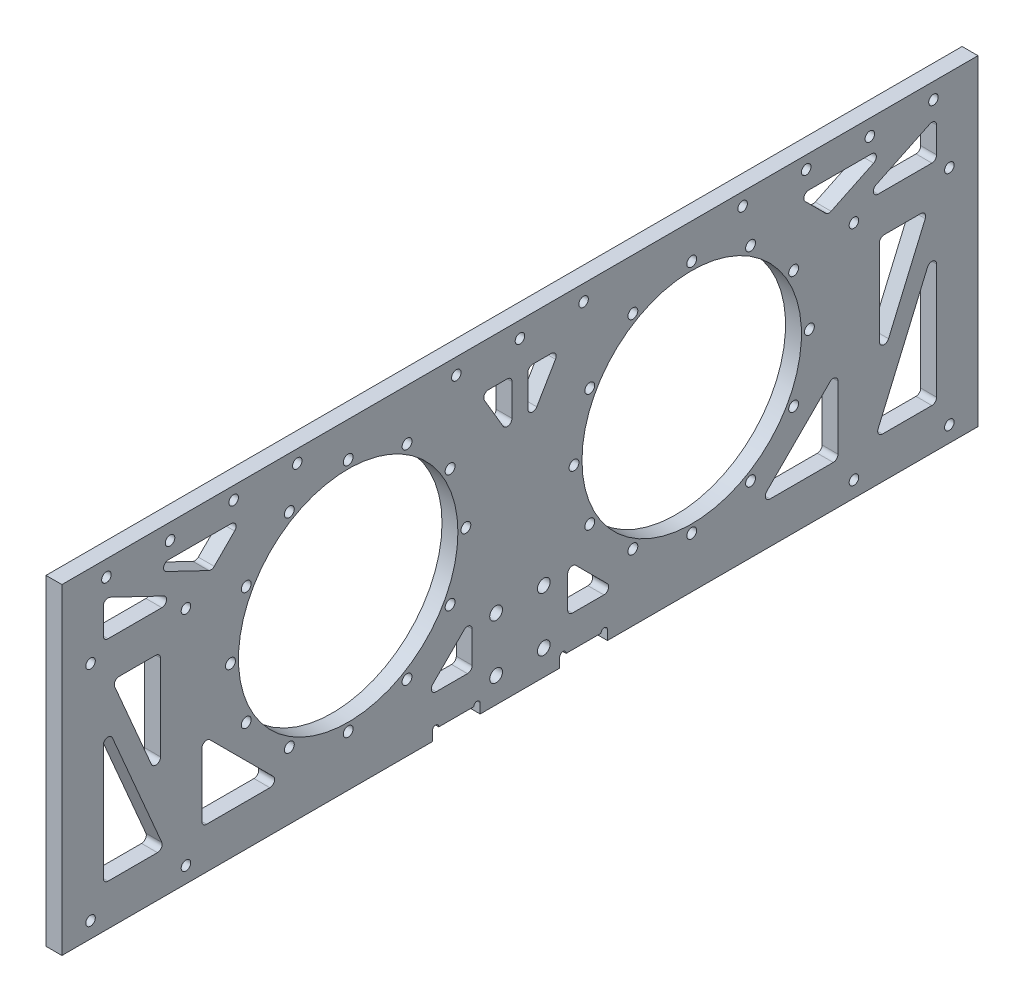
SolidWorks part; units mm, degrees
material "Thornel Mat VMA"
ref_plane "前视基准面" through (0, 0, 0) normal (0, 0, 1) x (1, 0, 0)
ref_plane "上视基准面" through (0, 0, 0) normal (0, 1, 0) x (1, 0, 0)
ref_plane "右视基准面" through (0, 0, 0) normal (1, 0, 0) x (0, 0, -1)
sketch "草图1" plane through (0, 0, 0) normal (1, 0, 0) x (0, 0, -1)
  line L0 (54, 48) -> (54, -53) construction
  line L1 (-90, -53) -> (198, -53)
  line L2 (-90, -53) -> (-90, 48)
  line L3 (-90, 48) -> (198, 48)
  line L4 (198, -53) -> (198, 48)
  line L5 (-36, 44) -> (-16, 44) construction
  line L6 (46.5, -45) -> (61.5, -45) construction
  line L7 (46.5, -45) -> (46.5, -28) construction
  line L8 (46.5, -28) -> (61.5, -28) construction
  line L9 (61.5, -45) -> (61.5, -28) construction
  line L10 (46.5, -45) -> (61.5, -28) construction
  line L11 (46.5, -28) -> (61.5, -45) construction
  line L12 (144, 44) -> (124, 44) construction
  circle A0 centre (0, 0) radius 34.5
  circle A1 centre (0, 0) radius 37 construction
  circle A2 centre (0, 37) radius 1.55
  circle A3 centre (18.5, 32.0429) radius 1.55
  circle A4 centre (32.0429, 18.5) radius 1.55
  circle A5 centre (37, 0) radius 1.55
  circle A6 centre (32.0429, -18.5) radius 1.55
  circle A7 centre (18.5, -32.0429) radius 1.55
  circle A8 centre (0, -37) radius 1.55
  circle A9 centre (-18.5, -32.0429) radius 1.55
  circle A10 centre (-32.0429, -18.5) radius 1.55
  circle A11 centre (-37, 0) radius 1.55
  circle A12 centre (-32.0429, 18.5) radius 1.55
  circle A13 centre (-18.5, 32.0429) radius 1.55
  circle A14 centre (126.5, 32.0429) radius 1.55
  circle A15 centre (140.0429, 18.5) radius 1.55
  circle A16 centre (145, 0) radius 1.55
  circle A17 centre (140.0429, -18.5) radius 1.55
  circle A18 centre (126.5, -32.0429) radius 1.55
  circle A19 centre (108, -37) radius 1.55
  circle A20 centre (89.5, -32.0429) radius 1.55
  circle A21 centre (75.9571, -18.5) radius 1.55
  circle A22 centre (71, 0) radius 1.55
  circle A23 centre (75.9571, 18.5) radius 1.55
  circle A24 centre (89.5, 32.0429) radius 1.55
  circle A25 centre (108, 37) radius 1.55
  circle A26 centre (108, 0) radius 37 construction
  circle A27 centre (108, 0) radius 34.5
  circle A28 centre (0, 0) radius 46 construction
  circle A29 centre (108, 0) radius 46 construction
  circle A30 centre (61.5, -28) radius 2
  circle A31 centre (46.5, -28) radius 2
  circle A32 centre (46.5, -45) radius 2
  circle A33 centre (61.5, -45) radius 2
  circle A34 centre (-16, 44) radius 1.5
  circle A35 centre (-36, 44) radius 1.5
  circle A36 centre (124, 44) radius 1.5
  circle A37 centre (144, 44) radius 1.5
  point P63 (54, -36.5)
  dimension "D1" = 69
  dimension "D2" = 74
  dimension "D4" = 3.1
  dimension "D9" = 92
  dimension "D13" = 4
  dimension "D17" = 3
  dimension "D5" = 53
  dimension "D6" = 48
  dimension "D7" = 90
  dimension "D8" = 108
  dimension "D10" = 25
  dimension "D11" = 17
  dimension "D12" = 15
  dimension "D14" = 70
  dimension "D15" = 20
  dimension "D16" = 4
  dimension "D3" = 12
extrude "凸台-拉伸1" add sketch "草图1" along normal blind 5
sketch "草图2" plane through (5, 0, 0) normal (1, 0, 0) x (0, 0, -1)
  line L0 (-76, 43) -> (-56, 43) construction
  line L1 (54, 48) -> (54, -53) construction
  line L2 (198, 48) -> (-90, 48) construction
  line L3 (-90, -53) -> (198, -53) construction
  line L4 (184, 43) -> (164, 43) construction
  line L5 (-90, 48) -> (-90, -53) construction
  line L6 (34, 43) -> (54, 43) construction
  circle A0 centre (-76, 43) radius 1.5
  circle A1 centre (-56, 43) radius 1.5
  circle A2 centre (164, 43) radius 1.5
  circle A3 centre (184, 43) radius 1.5
  circle A4 centre (34, 43) radius 1.5
  circle A5 centre (54, 43) radius 1.5
  circle A6 centre (74, 43) radius 1.5
  dimension "D1" = 14
  dimension "D4" = 3
  dimension "D6" = 3
  dimension "D2" = 20
  dimension "D3" = 5
  dimension "D5" = 20
extrude "切除-拉伸1" cut sketch "草图2" against normal through all
sketch "草图3" plane through (5, 0, 0) normal (1, 0, 0) x (0, 0, -1)
  line L0 (-81, -48) -> (-51, -48) construction
  line L1 (-90, 48) -> (-90, -53) construction
  line L2 (-90, -53) -> (198, -53) construction
  line L3 (54, 48) -> (54, -53) construction
  line L4 (198, 48) -> (-90, 48) construction
  line L5 (-81, -48) -> (-81, 22) construction
  line L6 (-81, 22) -> (-51, 22) construction
  line L7 (-51, 22) -> (-51, -48) construction
  line L8 (159, 22) -> (159, -48) construction
  line L9 (189, 22) -> (159, 22) construction
  line L10 (189, -48) -> (189, 22) construction
  line L11 (189, -48) -> (159, -48) construction
  circle A0 centre (-81, -48) radius 1.5
  circle A1 centre (-51, -48) radius 1.5
  circle A2 centre (-81, 22) radius 1.5
  circle A3 centre (-51, 22) radius 1.5
  circle A4 centre (159, 22) radius 1.5
  circle A5 centre (189, 22) radius 1.5
  circle A6 centre (159, -48) radius 1.5
  circle A7 centre (189, -48) radius 1.5
  dimension "D3" = 3
  dimension "D1" = 9
  dimension "D2" = 5
  dimension "D4" = 30
  dimension "D5" = 70
extrude "切除-拉伸2" cut sketch "草图3" against normal blind 10
sketch "草图4" plane through (5, 0, 0) normal (1, 0, 0) x (0, 0, -1)
  line L0 (44.1226, 34) -> (50, 34)
  line L1 (51.5, 32.5) -> (51.5, 22.5085)
  line L2 (48.7071, 21.7479) -> (42.8297, 31.7395)
  line L3 (54, 48) -> (54, -53) construction
  line L4 (198, 48) -> (-90, 48) construction
  line L5 (-90, -53) -> (198, -53) construction
  line L6 (56.5, 32.5) -> (56.5, 22.5085)
  line L7 (63.8774, 34) -> (58, 34)
  line L8 (59.2929, 21.7479) -> (65.1703, 31.7395)
  line L9 (-77, -2.257) -> (-77, -38.5)
  line L10 (-81, 22) -> (-51, 22) construction
  line L11 (-81, 22) -> (-81, -48) construction
  line L12 (-81, -48) -> (-51, -48) construction
  line L13 (-51, 22) -> (-51, -48) construction
  line L14 (-75.5, -40) -> (-59.9673, -40)
  line L15 (-58.5886, -37.9091) -> (-74.1213, -1.6661)
  line L16 (-72.0327, 14) -> (-60.5, 14)
  line L17 (-59, 12.5) -> (-59, -14.4097)
  line L18 (-61.8787, -15.0006) -> (-73.4114, 11.9091)
  line L19 (-46, -18.6213) -> (-46, -38.5)
  line L20 (-44.5, -40) -> (-24.6213, -40)
  line L21 (-23.5607, -37.4393) -> (-43.4393, -17.5607)
  line L22 (-77, 35.6161) -> (-77, 27.5)
  line L23 (-75.5, 26) -> (-58.5914, 26)
  line L24 (-57.9423, 28.8523) -> (-74.8509, 36.9684)
  line L25 (-56.5432, 38) -> (-36.7559, 38)
  line L26 (-35.6952, 35.4393) -> (-42.1127, 29.0218)
  line L27 (-43.8225, 28.7302) -> (-57.1923, 35.1477)
  line L34 (27.6213, -40) -> (37.5, -40)
  line L35 (39, -38.5) -> (39, -28.6213)
  line L36 (36.4393, -27.5607) -> (26.5607, -37.4393)
  line L37 (71.5607, -27.5607) -> (81.4393, -37.4393)
  line L38 (69, -38.5) -> (69, -28.6213)
  line L39 (80.3787, -40) -> (70.5, -40)
  line L40 (159, 22) -> (159, -48) construction
  line L41 (189, -48) -> (159, -48) construction
  line L42 (189, 22) -> (189, -48) construction
  line L43 (189, 22) -> (159, 22) construction
  line L50 (151.8225, 28.7302) -> (165.1923, 35.1477)
  line L51 (143.6952, 35.4393) -> (150.1127, 29.0218)
  line L52 (164.5432, 38) -> (144.7559, 38)
  line L53 (165.9423, 28.8523) -> (182.8509, 36.9684)
  line L54 (183.5, 26) -> (166.5914, 26)
  line L55 (185, 35.6161) -> (185, 27.5)
  line L56 (131.5607, -37.4393) -> (151.4393, -17.5607)
  line L57 (152.5, -40) -> (132.6213, -40)
  line L58 (154, -18.6213) -> (154, -38.5)
  line L59 (169.8787, -15.0006) -> (181.4114, 11.9091)
  line L60 (167, 12.5) -> (167, -14.4097)
  line L61 (180.0327, 14) -> (168.5, 14)
  line L62 (166.5886, -37.9091) -> (182.1213, -1.6661)
  line L63 (183.5, -40) -> (167.9673, -40)
  line L64 (185, -2.257) -> (185, -38.5)
  arc A0 (51.5, 22.5085) -> (48.7071, 21.7479) centre (50, 22.5085) cw
  arc A1 (50, 34) -> (51.5, 32.5) centre (50, 32.5) cw
  arc A2 (44.1226, 34) -> (42.8297, 31.7395) centre (44.1226, 32.5) ccw
  arc A3 (58, 34) -> (56.5, 32.5) centre (58, 32.5) ccw
  arc A4 (56.5, 22.5085) -> (59.2929, 21.7479) centre (58, 22.5085) ccw
  arc A5 (63.8774, 34) -> (65.1703, 31.7395) centre (63.8774, 32.5) cw
  arc A7 (-77, -38.5) -> (-75.5, -40) centre (-75.5, -38.5) ccw
  arc A8 (-59.9673, -40) -> (-58.5886, -37.9091) centre (-59.9673, -38.5) ccw
  arc A9 (-77, -2.257) -> (-74.1213, -1.6661) centre (-75.5, -2.257) cw
  arc A10 (-59, -14.4097) -> (-61.8787, -15.0006) centre (-60.5, -14.4097) cw
  arc A11 (-60.5, 14) -> (-59, 12.5) centre (-60.5, 12.5) cw
  arc A12 (-72.0327, 14) -> (-73.4114, 11.9091) centre (-72.0327, 12.5) ccw
  arc A14 (-24.6213, -40) -> (-23.5607, -37.4393) centre (-24.6213, -38.5) ccw
  arc A15 (-46, -38.5) -> (-44.5, -40) centre (-44.5, -38.5) ccw
  arc A16 (-46, -18.6213) -> (-43.4393, -17.5607) centre (-44.5, -18.6213) cw
  arc A23 (-36.7559, 38) -> (-35.6952, 35.4393) centre (-36.7559, 36.5) cw
  arc A24 (-42.1127, 29.0218) -> (-43.8225, 28.7302) centre (-43.1734, 30.0825) cw
  arc A25 (-56.5432, 38) -> (-57.1923, 35.1477) centre (-56.5432, 36.5) ccw
  arc A26 (-58.5914, 26) -> (-57.9423, 28.8523) centre (-58.5914, 27.5) ccw
  arc A27 (-77, 27.5) -> (-75.5, 26) centre (-75.5, 27.5) ccw
  arc A28 (-77, 35.6161) -> (-74.8509, 36.9684) centre (-75.5, 35.6161) cw
  arc A29 (27.6213, -40) -> (26.5607, -37.4393) centre (27.6213, -38.5) cw
  arc A30 (37.5, -40) -> (39, -38.5) centre (37.5, -38.5) ccw
  arc A31 (39, -28.6213) -> (36.4393, -27.5607) centre (37.5, -28.6213) ccw
  arc A32 (69, -28.6213) -> (71.5607, -27.5607) centre (70.5, -28.6213) cw
  arc A33 (70.5, -40) -> (69, -38.5) centre (70.5, -38.5) cw
  arc A34 (80.3787, -40) -> (81.4393, -37.4393) centre (80.3787, -38.5) ccw
  arc A35 (185, 35.6161) -> (182.8509, 36.9684) centre (183.5, 35.6161) ccw
  arc A36 (185, 27.5) -> (183.5, 26) centre (183.5, 27.5) cw
  arc A37 (166.5914, 26) -> (165.9423, 28.8523) centre (166.5914, 27.5) cw
  arc A38 (164.5432, 38) -> (165.1923, 35.1477) centre (164.5432, 36.5) cw
  arc A39 (150.1127, 29.0218) -> (151.8225, 28.7302) centre (151.1734, 30.0825) ccw
  arc A40 (144.7559, 38) -> (143.6952, 35.4393) centre (144.7559, 36.5) ccw
  arc A47 (154, -18.6213) -> (151.4393, -17.5607) centre (152.5, -18.6213) ccw
  arc A48 (154, -38.5) -> (152.5, -40) centre (152.5, -38.5) cw
  arc A49 (132.6213, -40) -> (131.5607, -37.4393) centre (132.6213, -38.5) cw
  arc A50 (180.0327, 14) -> (181.4114, 11.9091) centre (180.0327, 12.5) cw
  arc A51 (168.5, 14) -> (167, 12.5) centre (168.5, 12.5) ccw
  arc A52 (167, -14.4097) -> (169.8787, -15.0006) centre (168.5, -14.4097) ccw
  arc A53 (185, -2.257) -> (182.1213, -1.6661) centre (183.5, -2.257) ccw
  arc A54 (167.9673, -40) -> (166.5886, -37.9091) centre (167.9673, -38.5) cw
  arc A55 (185, -38.5) -> (183.5, -40) centre (183.5, -38.5) cw
  point P11 (51.5, 17)
  point P14 (51.5, 34)
  point P17 (41.5, 34)
  point P73 (-21, -40)
  point P76 (-46, -40)
  point P79 (-46, -15)
  point P97 (-33.1346, 38)
  point P102 (-63.1346, 38)
  point P105 (-52, 26)
  point P108 (-77, 26)
  point P111 (-77, 38)
  point P115 (24, -40)
  point P118 (39, -40)
  point P130 (69, -40)
  point P131 (84, -40)
  point P199 (185, 38)
  point P200 (185, 26)
  point P201 (160, 26)
  point P202 (171.1346, 38)
  point P203 (141.1346, 38)
  point P207 (154, -15)
  point P208 (154, -40)
  point P209 (129, -40)
  dimension "D5" = 1.5
  dimension "D13" = 1.5
  dimension "D26" = 1.5
  dimension "D30" = 1.5
  dimension "D23" = 1.5
  dimension "D1" = 2.5
  dimension "D2" = 14
  dimension "D3" = 10
  dimension "D4" = 17
  dimension "D6" = 8
  dimension "D7" = 4
  dimension "D8" = 8
  dimension "D9" = 16
  dimension "D10" = 3
  dimension "D11" = 3
  dimension "D12" = 3
  dimension "D14" = 5
  dimension "D15" = 25
  dimension "D16" = 25
  dimension "D17" = 10
  dimension "D18" = 4
  dimension "D19" = 25
  dimension "D20" = 6
  dimension "D21" = 45
  dimension "D22" = 30
  dimension "D27" = 15
  dimension "D28" = 45
  dimension "D29" = 15
extrude "切除-拉伸3" cut sketch "草图4" against normal through all
sketch "草图6" plane through (5, 0, 0) normal (1, 0, 0) x (0, 0, -1)
  line L0 (41.5, -53) -> (41.5, -50)
  line L1 (-90, -53) -> (198, -53) construction
  line L5 (54, 48) -> (54, -53) construction
  line L6 (198, 48) -> (-90, 48) construction
  line L7 (39.5, -50) -> (28.5, -50)
  line L8 (26.5, -50) -> (26.5, -53)
  line L9 (26.5, -53) -> (41.5, -53)
  line L13 (81.5, -53) -> (66.5, -53)
  line L14 (81.5, -50) -> (81.5, -53)
  line L15 (68.5, -50) -> (79.5, -50)
  line L16 (66.5, -53) -> (66.5, -50)
  arc A0 (26.5, -50) -> (28.5, -50) centre (27.5, -50) cw
  arc A1 (41.5, -50) -> (39.5, -50) centre (40.5, -50) ccw
  arc A2 (66.5, -50) -> (68.5, -50) centre (67.5, -50) cw
  arc A3 (81.5, -50) -> (79.5, -50) centre (80.5, -50) ccw
  dimension "D4" = 1
  dimension "D1" = 25
  dimension "D2" = 3
  dimension "D3" = 15
extrude "切除-拉伸4" cut sketch "草图6" against normal through all
